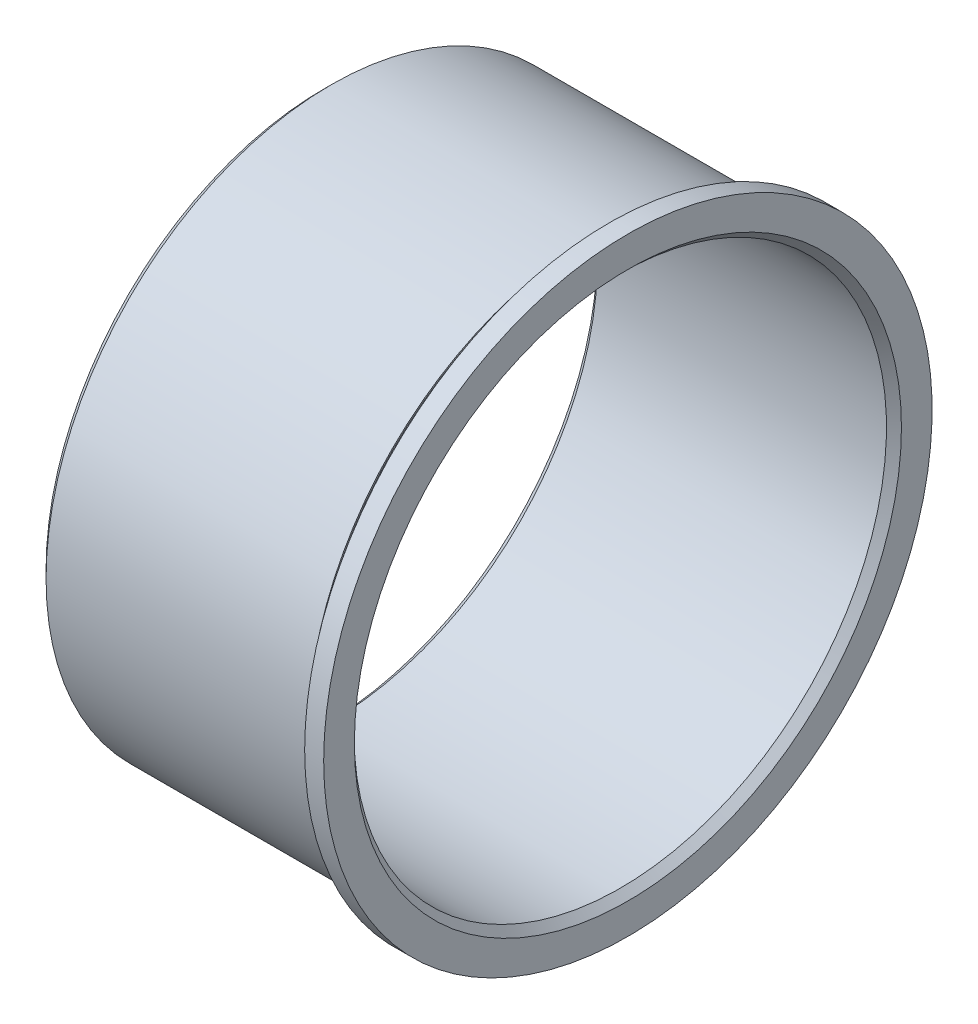
SolidWorks part; units mm, degrees
ref_plane "前视基准面" through (0, 0, 0) normal (0, 0, 1) x (1, 0, 0)
ref_plane "上视基准面" through (0, 0, 0) normal (0, 1, 0) x (1, 0, 0)
ref_plane "右视基准面" through (0, 0, 0) normal (1, 0, 0) x (0, 0, -1)
sketch "尺寸草图" plane through (0, 0, 0) normal (0, 0, 1) x (1, 0, 0)
  line L0 (-20, 0) -> (20, 0) construction
  line L1 (0, 0) -> (0, 35) construction
  line L2 (-20, 35.9657) -> (-19, 35)
  line L3 (-19, 35) -> (19, 35)
  line L4 (19, 35) -> (20, 35.9657)
  line L5 (20, 35.9657) -> (20, 40)
  line L6 (20, 40) -> (17.5, 40)
  line L7 (17.5, 40) -> (17.5, 37.3)
  line L8 (17.5, 37.3) -> (15.5, 37.3)
  line L9 (15.5, 37.3) -> (15.5, 37.5)
  line L10 (15.5, 37.5) -> (-19, 37.5)
  line L11 (-19, 37.5) -> (-20, 36.5)
  line L12 (-20, 36.5) -> (-20, 35.9657)
  dimension "D1" = 44
  dimension "内径d1" = 70
  dimension "倒角C1" = 1
  dimension "D2" = 0.2
  dimension "外径d2" = 75
  dimension "翻边外径d3" = 80
  dimension "宽度b1" = 40
  dimension "翻边宽度b2" = 2.5
  dimension "退刀槽宽度u" = 2
  dimension "倒角C2" = 1
  dimension "C2角度" = 45
revolve "旋转1" add sketch "尺寸草图" angle 360 about L0
